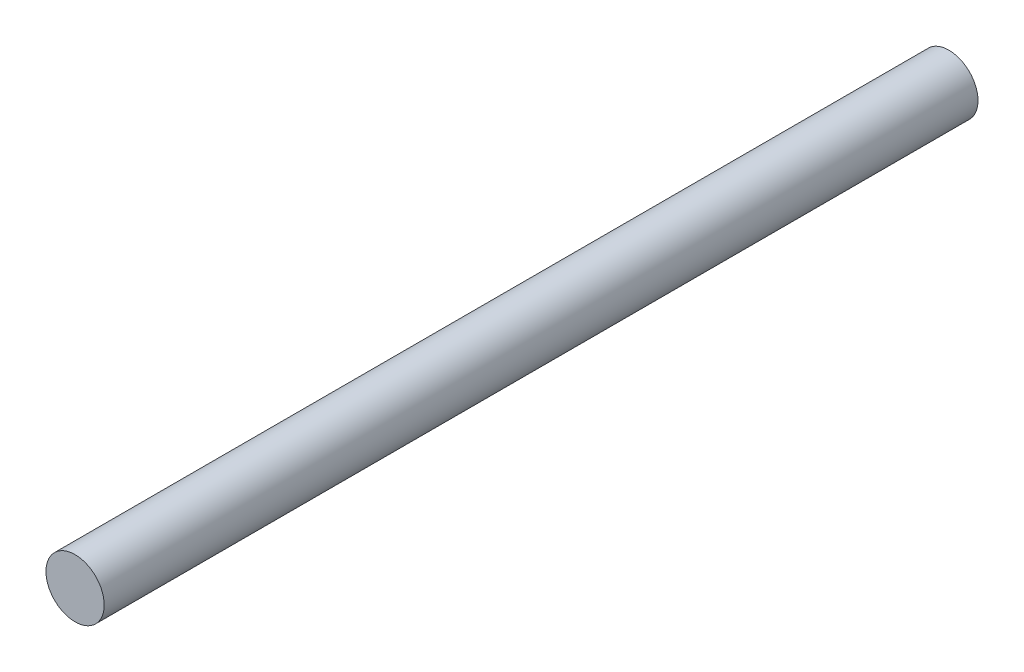
SolidWorks part; units mm, degrees
ref_plane "Front Plane" through (0, 0, 0) normal (0, 0, 1) x (1, 0, 0)
ref_plane "Top Plane" through (0, 0, 0) normal (0, 1, 0) x (1, 0, 0)
ref_plane "Right Plane" through (0, 0, 0) normal (1, 0, 0) x (0, 0, -1)
sketch "Sketch1" plane through (0, 0, 0) normal (0, 0, 1) x (1, 0, 0)
  circle A0 centre (-37.2391, -4.1) radius 0.6
extrude "Boss-Extrude1" add sketch "Sketch1" against normal up to surface (18 mm away)
